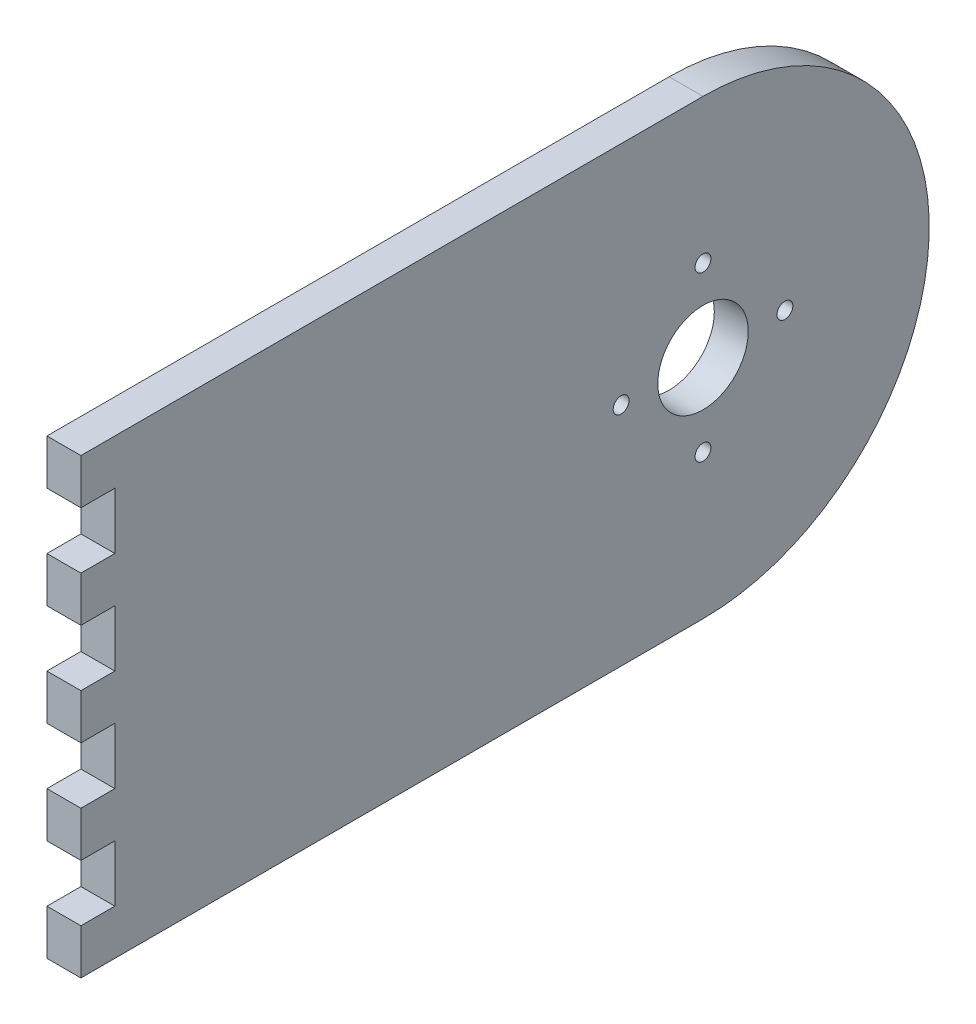
SolidWorks part; units mm, degrees
ref_plane "Front Plane" through (0, 0, 0) normal (0, 0, 1) x (1, 0, 0)
ref_plane "Top Plane" through (0, 0, 0) normal (0, 1, 0) x (1, 0, 0)
ref_plane "Right Plane" through (0, 0, 0) normal (1, 0, 0) x (0, 0, -1)
sketch "Sketch1" plane through (0, 0, 0) normal (1, 0, 0) x (0, 0, -1)
  line L0 (0, 20) -> (-55, 20)
  line L1 (-55, 20) -> (-55, 16)
  line L2 (-55, -20) -> (0, -20)
  line L3 (-55, 16) -> (-52, 16)
  line L4 (-52, 16) -> (-52, 11)
  line L5 (-52, 11) -> (-55, 11)
  line L6 (-55, 7) -> (-52, 7)
  line L7 (-52, 7) -> (-52, 2)
  line L8 (-52, 2) -> (-55, 2)
  line L9 (-55, -16) -> (-52, -16)
  line L10 (-52, -16) -> (-52, -11)
  line L11 (-52, -11) -> (-55, -11)
  line L12 (-55, -7) -> (-52, -7)
  line L13 (-52, -7) -> (-52, -2)
  line L14 (-52, -2) -> (-55, -2)
  line L15 (-55, 11) -> (-55, 7)
  line L16 (-55, 2) -> (-55, -2)
  line L17 (-55, -7) -> (-55, -11)
  line L18 (-55, -16) -> (-55, -20)
  circle A0 centre (0, 0) radius 4
  circle A1 centre (-7.24, 0) radius 0.7
  circle A2 centre (0, 7.24) radius 0.7
  circle A3 centre (7.24, 0) radius 0.7
  circle A4 centre (0, -7.24) radius 0.7
  arc A7 (0, -20) -> (0, 20) centre (0, 0) ccw
  point P18 (0, 0)
  dimension "D1" = 8
  dimension "D2" = 1.4
  dimension "D5" = 40
  dimension "D3" = 7.24
  dimension "D6" = 55
  dimension "D7" = 4
  dimension "D8" = 3
  dimension "D4" = 4
extrude "Boss-Extrude1" add sketch "Sketch1" along normal blind 3
